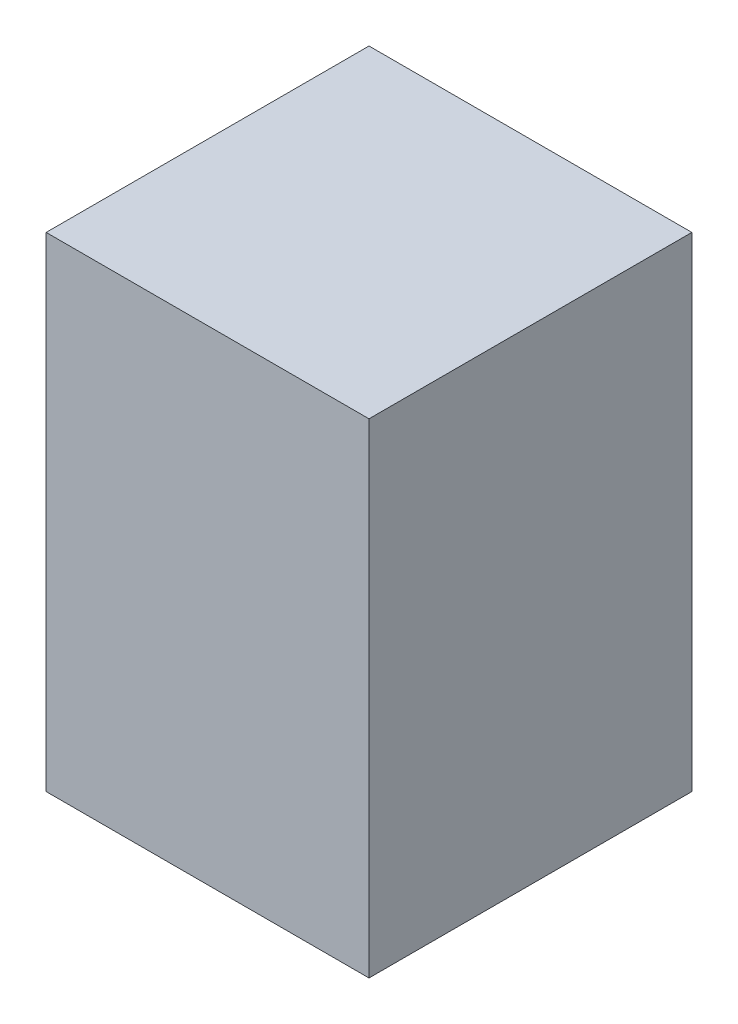
SolidWorks part; units mm, degrees
ref_plane "Front Plane" through (0, 0, 0) normal (0, 0, 1) x (1, 0, 0)
ref_plane "Top Plane" through (0, 0, 0) normal (0, 1, 0) x (1, 0, 0)
ref_plane "Right Plane" through (0, 0, 0) normal (1, 0, 0) x (0, 0, -1)
other "Configuration Table"
sketch "Sketch1" plane through (0, 0, 0) normal (0, 0, 1) x (1, 0, 0)
  line L1 (60, 0) -> (140, 0)
  line L2 (60, 0) -> (60, 120)
  line L3 (60, 120) -> (140, 120)
  line L4 (140, 0) -> (140, 120)
extrude "STORE_ayak_1_1" add sketch "Sketch1" against normal blind 80 from offset 40 separate body
